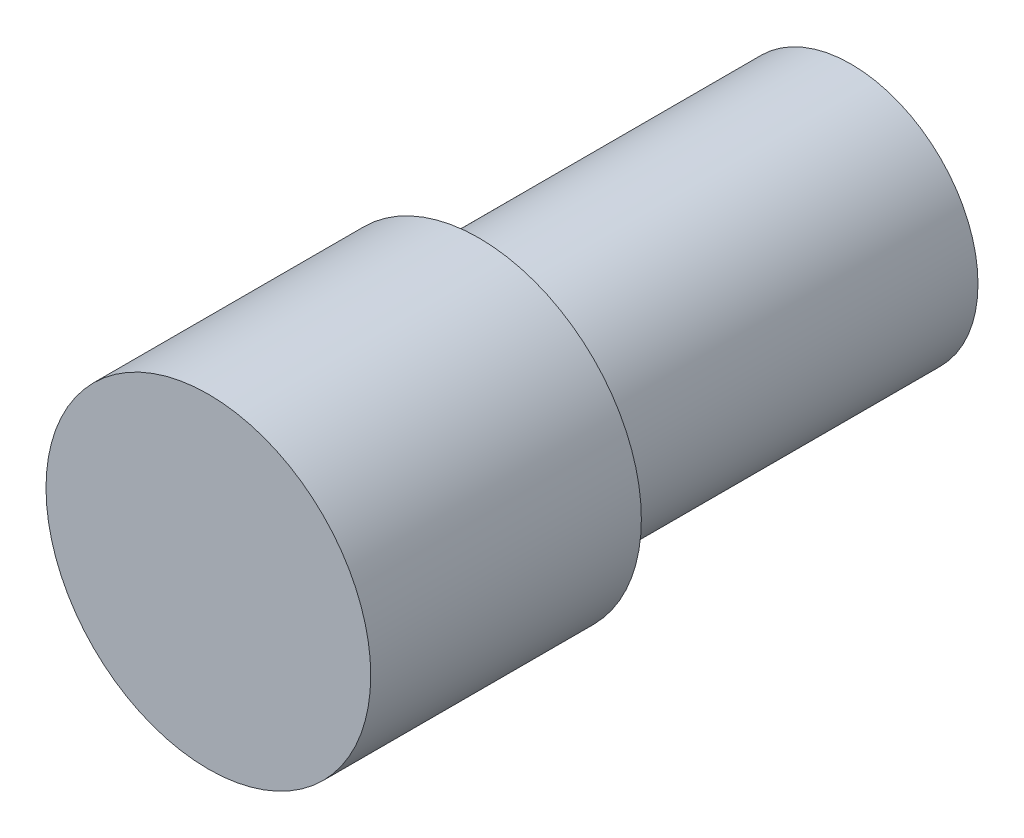
SolidWorks part; units mm, degrees
ref_plane "Front Plane" through (0, 0, 0) normal (0, 0, 1) x (1, 0, 0)
ref_plane "Top Plane" through (0, 0, 0) normal (0, 1, 0) x (1, 0, 0)
ref_plane "Right Plane" through (0, 0, 0) normal (1, 0, 0) x (0, 0, -1)
sketch "Sketch1" plane through (0, 0, 0) normal (0, 0, 1) x (1, 0, 0)
  circle A0 centre (0, 0) radius 6
  dimension "D1" = 12
extrude "Boss-Extrude1" add sketch "Sketch1" along normal blind 10
sketch "Sketch3" plane through (0, 0, 0) normal (0, 0, -1) x (-1, 0, 0)
  circle A0 centre (0, 0) radius 4.69
  dimension "D1" = 9.38
extrude "Boss-Extrude2" add sketch "Sketch3" along normal blind 13.75
sketch "Sketch4" plane through (0, 0, -13.75) normal (0, 0, -1) x (-1, 0, 0)
  circle A0 centre (0, 0) radius 1.15
  dimension "D1" = 2.3
extrude "Cut-Extrude1" cut sketch "Sketch4" against normal blind 13.75
ref_plane "Plane1" through (0, 5, 0) normal (0, 1, 0) x (1, 0, 0)
